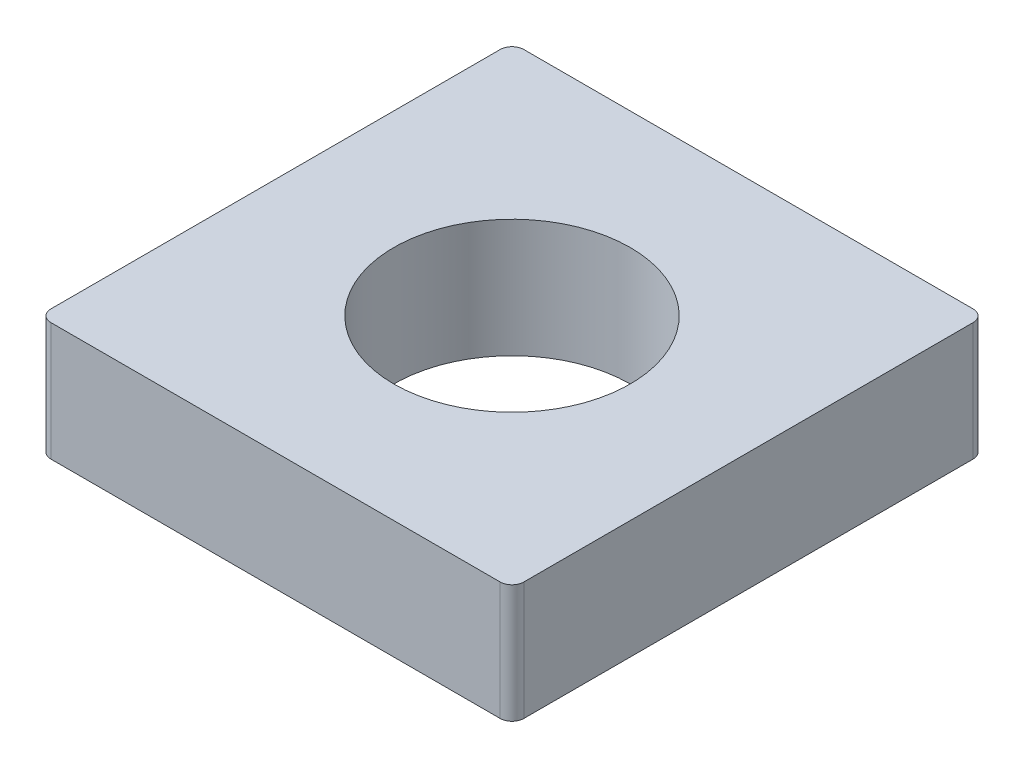
SolidWorks part; units mm, degrees
material "铸造碳钢"
ref_plane "Front" through (0, 0, 0) normal (0, 0, 1) x (1, 0, 0)
ref_plane "Top" through (0, 0, 0) normal (0, 1, 0) x (1, 0, 0)
ref_plane "Right" through (0, 0, 0) normal (1, 0, 0) x (0, 0, -1)
sketch "草图1" plane through (0, 0, 0) normal (0, 1, 0) x (1, 0, 0)
  line L1 (-4, 4) -> (4, 4)
  line L2 (-4, 4) -> (-4, -4)
  line L3 (-4, -4) -> (4, -4)
  line L4 (4, 4) -> (4, -4)
  line L5 (0, -4) -> (0, 4) construction
  line L6 (-4, 0) -> (4, 0) construction
  circle A0 centre (0, 0) radius 2
  point P0 (0, 0)
  dimension "螺丝孔直径" = 4
  dimension "螺母长度" = 8
  dimension "螺母宽度" = 8
extrude "凸台-拉伸1" add sketch "草图1" along normal mid plane 2
fillet "圆角1" radius 0.2 4 edges at (-4, 0, -4) (4, 0, -4) (4, 0, 4) (-4, 0, 4)
other "冻结***"
